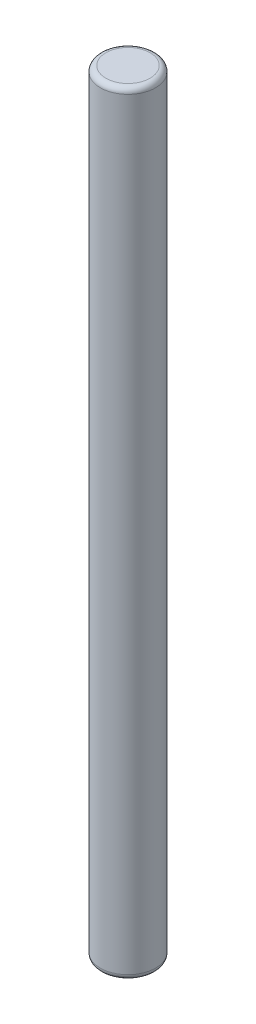
SolidWorks part; units mm, degrees
ref_plane "前视基准面" through (0, 0, 0) normal (0, 0, 1) x (1, 0, 0)
ref_plane "上视基准面" through (0, 0, 0) normal (0, 1, 0) x (1, 0, 0)
ref_plane "右视基准面" through (0, 0, 0) normal (1, 0, 0) x (0, 0, -1)
sketch "草图2" plane through (0, 0, 0) normal (0, 1, 0) x (1, 0, 0)
  circle A0 centre (0, 0) radius 2.5
  dimension "D1" = 5
extrude "凸台-拉伸1" add sketch "草图2" along normal blind 70
fillet "圆角4" radius 0.5 1 edges at (0, 0, 2.5)
fillet "圆角5" radius 0.5 1 edges at (0, 70, 2.5)
